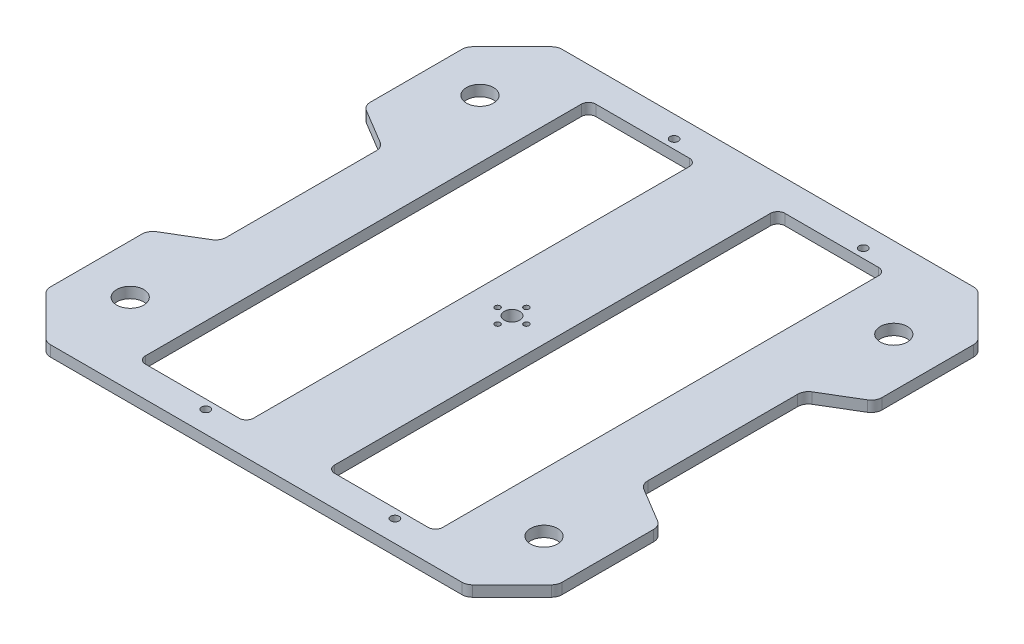
SolidWorks part; units mm, degrees
ref_plane "Plan de face" through (0, 0, 0) normal (0, 0, 1) x (1, 0, 0)
ref_plane "Plan de dessus" through (0, 0, 0) normal (0, 1, 0) x (1, 0, 0)
ref_plane "Plan de droite" through (0, 0, 0) normal (1, 0, 0) x (0, 0, -1)
sketch "Esquisse1" plane through (0, 0, 0) normal (0, 1, 0) x (1, 0, 0)
  line L0 (150, -150) -> (150, 150) construction
  line L1 (150, 150) -> (0, 150) construction
  line L2 (-150, 150) -> (-150, -150) construction
  line L3 (-150, 150) -> (150, 150) construction
  line L4 (150, 0) -> (-150, 0) construction
  line L5 (150, -150) -> (-150, -150) construction
  line L6 (0, 150) -> (0, -150) construction
  line L7 (-150, 0) -> (-150, 120)
  line L8 (0, 150) -> (-120, 150)
  line L9 (-150, 120) -> (-120, 150)
  line L10 (0, 150) -> (120, 150)
  line L11 (150, 0) -> (150, 120)
  line L12 (150, 120) -> (120, 150)
  line L13 (-150, 0) -> (-150, -120)
  line L14 (0, -150) -> (-120, -150)
  line L15 (-120, -150) -> (-150, -120)
  line L16 (150, 0) -> (150, -120)
  line L17 (0, -150) -> (120, -150)
  line L18 (120, -150) -> (150, -120)
  dimension "D1" = 42.4264
  dimension "D2" = 240
  dimension "D3" = 120
  dimension "D4" = 42.4264
  dimension "D5" = 120
  dimension "D6" = 300
  dimension "D7" = 300
  dimension "D8" = 30
extrude "Boss.-Extru.1" add sketch "Esquisse1" along normal blind 6
sketch "Esquisse12" plane through (0, 6, 0) normal (0, 1, 0) x (1, 0, 0)
  line L0 (0, 0) -> (-150, 0) construction
  line L1 (-150, 120) -> (-150, -120) construction
  line L2 (-150, 0) -> (-150, 95) construction
  line L3 (-150, 95) -> (-100, 95) construction
  line L4 (-100, 95) -> (-114.854, 97.0876) construction
  circle A1 centre (-114.854, 97.0876) radius 7.5
  dimension "D1" = 150
  dimension "D5" = 15
  dimension "D3" = 50
  dimension "D4" = 8
  dimension "D2" = 95
extrude "Enlèv. mat.-Extru.10" cut sketch "Esquisse12" against normal up to next
mirror "Symétrie9" about plane through (0, 0, 0) normal (1, 0, 0) of "Enlèv. mat.-Extru.10"
mirror "Symétrie10" about plane through (0, 0, 0) normal (0, 0, 1) of "Symétrie9", "Enlèv. mat.-Extru.10"
sketch "Esquisse13" plane through (0, 6, 0) normal (0, 1, 0) x (1, 0, 0)
  line L0 (0, 0) -> (8, 0) construction
  line L1 (0, 0) -> (0, -8) construction
  line L2 (0, 0) -> (0, 8) construction
  line L3 (0, 0) -> (-8, 0) construction
  circle A0 centre (0, 0) radius 4.3
  circle A1 centre (8, 0) radius 1.5
  circle A2 centre (0, -8) radius 1.5
  circle A3 centre (0, 8) radius 1.5
  circle A4 centre (-8, 0) radius 1.5
  dimension "D1" = 8
  dimension "D2" = 8
extrude "Enlèv. mat.-Extru.11" cut sketch "Esquisse13" against normal up to next
sketch "Esquisse14" plane through (0, 6, 0) normal (0, 1, 0) x (1, 0, 0)
  line L0 (0, -150) -> (52.5, -150) construction
  line L1 (-120, -150) -> (120, -150) construction
  line L2 (52.5, -150) -> (52.5, -125) construction
  line L3 (52.5, -125) -> (82.5, -125)
  line L4 (82.5, -125) -> (82.5, 125)
  line L5 (82.5, 125) -> (22.5, 125)
  line L6 (22.5, 125) -> (22.5, -125)
  line L7 (22.5, -125) -> (52.5, -125)
  dimension "D1" = 52.5
  dimension "D2" = 25
  dimension "D3" = 30
  dimension "D4" = 250
  dimension "D5" = 60
extrude "Enlèv. mat.-Extru.12" cut sketch "Esquisse14" against normal up to next
fillet "Congé1" radius 4 4 edges at (22.5, 3, 125) (82.5, 3, 125) (82.5, 3, -125) (22.5, 3, -125)
mirror "Symétrie11" about plane through (0, 0, 0) normal (1, 0, 0) of "Enlèv. mat.-Extru.12", "Congé1"
sketch "Esquisse15" plane through (0, 6, 0) normal (0, 1, 0) x (1, 0, 0)
  line L2 (-22.5, 125) -> (-22.5, 121) construction
  line L3 (-40, 125) -> (-40, 130) construction
  line L4 (-40, 130) -> (-40, -130) construction
  arc A0 (-22.5, 121) -> (-26.5, 125) centre (-26.5, 121) ccw construction
  circle A1 centre (-40, 130) radius 2.3
  circle A2 centre (-40, -130) radius 2.3
  dimension "D3" = 5
  dimension "D1" = 4
  dimension "D2" = 17.5
extrude "Enlèv. mat.-Extru.13" cut sketch "Esquisse15" against normal up to next and the other way through all
pattern_linear "Répétition linéaire1" count 2 spacing 105 along (1, 0, 0) of "Enlèv. mat.-Extru.13"
sketch "Esquisse16" plane through (0, 6, 0) normal (0, 1, 0) x (1, 0, 0)
  line L0 (-150, 0) -> (-142, 0) construction
  line L1 (-150, 120) -> (-150, -120) construction
  line L2 (-142, 0) -> (-142, 120)
  line L3 (-142, 120) -> (-150, 120)
  line L4 (-150, 120) -> (-150, -120)
  line L5 (-150, -120) -> (-142, -120)
  line L6 (-142, -120) -> (-142, 0)
  line L7 (-135, -135) -> (-129.3431, -129.3431) construction
  line L8 (-150, -120) -> (-120, -150) construction
  line L9 (-126.5628, 132.1235) -> (-132.2197, 137.7803) construction
  line L10 (-120, -150) -> (-120, -142)
  line L11 (-120, -142) -> (120, -142)
  line L12 (120, -142) -> (120, -150)
  line L13 (129.3431, -129.3431) -> (116.6863, -142)
  line L14 (135, -135) -> (129.3431, -129.3431) construction
  line L15 (120, -150) -> (150, -120) construction
  line L16 (129.3431, -129.3431) -> (142, -116.6863)
  line L17 (150, -120) -> (142, -120)
  line L18 (142, -120) -> (142, 120)
  line L19 (142, 120) -> (150, 120)
  line L20 (150, -120) -> (150, 120) construction
  line L21 (150, 120) -> (120, 150) construction
  line L22 (120, 150) -> (120, 142)
  line L23 (120, 142) -> (-120, 142)
  line L24 (-120, 142) -> (-120, 150)
  line L25 (-120, 150) -> (-150, 120) construction
  line L26 (120, 150) -> (-120, 150) construction
  line L27 (-129.3431, -129.3431) -> (-142, -116.6863)
  line L28 (-129.3431, -129.3431) -> (-116.6863, -142)
  line L29 (-126.5628, 132.1235) -> (-116.6863, 142)
  line L30 (135, 135) -> (129.3431, 129.3431) construction
  line L31 (-126.5628, 132.1235) -> (-142, 116.6863)
  line L32 (129.3431, 129.3431) -> (116.6863, 142)
  line L33 (129.3431, 129.3431) -> (142, 116.6863)
  line L34 (150, -120) -> (120, -150)
  line L35 (150, -120) -> (150, 120)
  line L36 (120, 150) -> (150, 120)
  line L37 (120, 150) -> (-120, 150)
  line L38 (-150, 120) -> (-120, 150)
extrude "Enlèv. mat.-Extru.14" cut sketch "Esquisse16" against normal blind 24
sketch "Esquisse17" plane through (0, 6, 0) normal (0, 1, 0) x (1, 0, 0)
  line L0 (-142, 0) -> (-117, 0) construction
  line L1 (-142, -116.6863) -> (-142, 116.6863) construction
  line L3 (-117, 45) -> (-142, 45)
  line L4 (-142, 45) -> (-142, -45)
  line L5 (-142, -45) -> (-117, -45)
  line L7 (-142, 45) -> (-117, 45)
  line L8 (-117, -45) -> (-142, -45)
  line L9 (-117, 45) -> (-142, 45)
  line L10 (-142, -45) -> (-117, -45)
  line L11 (-142, 45) -> (-117, 45)
  line L12 (-117, -45) -> (-142, -45)
  line L13 (-117, 0) -> (-117, -45)
  line L14 (-117, 0) -> (-117, 45)
  line L15 (-142, -45) -> (-142, -60)
  line L16 (-117, -45) -> (-142, -60)
  line L17 (-142, 45) -> (-142, 60)
  line L18 (-142, 60) -> (-117, 45)
  line M33 (-142, 116.6863) -> (-142, -116.6863)
  dimension "D1" = 45
  dimension "D2" = 25
  dimension "D3" = 15
  dimension "D4" = 15
extrude "Enlèv. mat.-Extru.15" cut sketch "Esquisse17" against normal up to next contours L16 L5 M33 | L0 L4 L5 L13 | L0 L14 L3 M33 | L18 L3 M33
mirror "Symétrie12" about plane through (0, 0, 0) normal (1, 0, 0) of "Enlèv. mat.-Extru.15"
fillet "Congé2" radius 6 16 edges at (-116.6863, 3, 142) (-142, 3, 116.6863) (-142, 3, 60) (-117, 3, 45) (116.6863, 3, 142) (142, 3, 116.6863) (142, 3, 60) (117, 3, 45) (117, 3, -45) (142, 3, -60) (142, 3, -116.6863) (116.6863, 3, -142) (-116.6863, 3, -142) (-142, 3, -116.6863) (-142, 3, -60) (-117, 3, -45)
